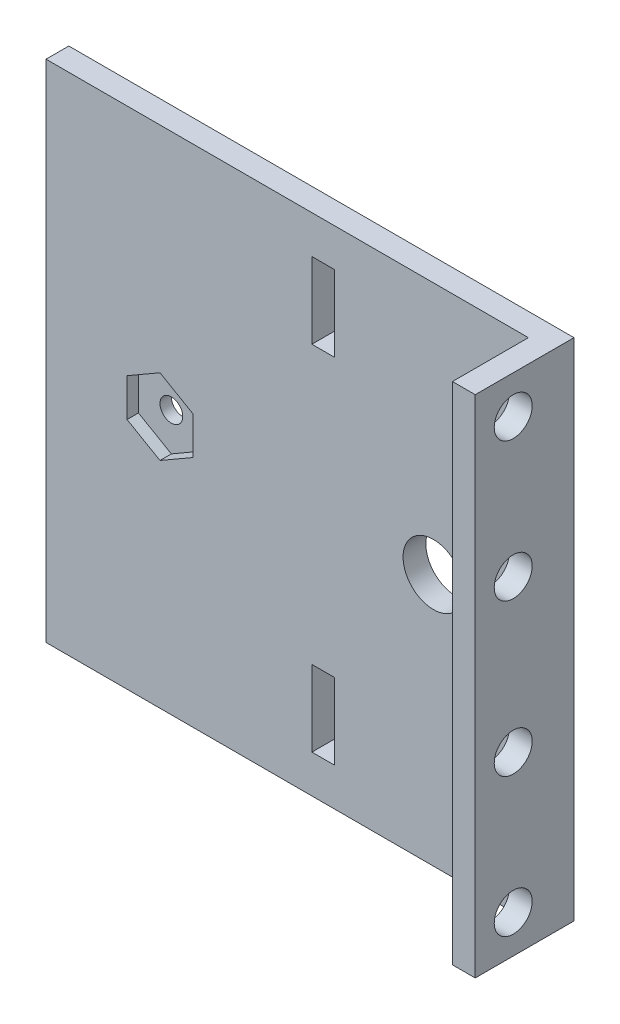
SolidWorks part; units mm, degrees
ref_plane "Front Plane" through (0, 0, 0) normal (0, 0, 1) x (1, 0, 0)
ref_plane "Top Plane" through (0, 0, 0) normal (0, 1, 0) x (1, 0, 0)
ref_plane "Right Plane" through (0, 0, 0) normal (1, 0, 0) x (0, 0, -1)
sketch "Sketch1" plane through (0, 0, 0) normal (0, 0, 1) x (1, 0, 0)
  line L1 (-33.25, 33.25) -> (33.25, 33.25)
  line L2 (-33.25, 33.25) -> (-33.25, -33.25)
  line L3 (-33.25, -33.25) -> (33.25, -33.25)
  line L4 (33.25, 33.25) -> (33.25, -33.25)
  line L5 (-33.25, 33.25) -> (33.25, -33.25) construction
  line L6 (-33.25, -33.25) -> (33.25, 33.25) construction
  circle A0 centre (17.75, 0) radius 4
  point P0 (0, 0)
  dimension "D4" = 8
  dimension "D1" = 66.5
  dimension "D2" = 66.5
  dimension "D3" = 15.5
  dimension "D5" = 33.25
extrude "Boss-Extrude1" add sketch "Sketch1" along normal blind 3
sketch "Sketch3" plane through (0, 0, 3) normal (0, 0, 1) x (1, 0, 0)
  line L0 (33.25, 33.25) -> (-33.25, 33.25) construction
  line L1 (33.25, -33.25) -> (30.25, -33.25)
  line L2 (33.25, -33.25) -> (33.25, 33.25)
  line L3 (33.25, 33.25) -> (30.25, 33.25)
  line L4 (30.25, -33.25) -> (30.25, 33.25)
  dimension "D1" = 3
extrude "Boss-Extrude2" add sketch "Sketch3" along normal blind 10
sketch "Sketch5" plane through (33.25, 0, 0) normal (1, 0, 0) x (0, 0, -1)
  line L0 (-13, -33.25) -> (0, -33.25) construction
  line L1 (-13, -33.25) -> (-13, 33.25) construction
  circle A0 centre (-8, -28.25) radius 2.5
  circle A1 centre (-8, -10) radius 2.5
  point P8 (-6.5, -33.25)
  dimension "D1" = 5
  dimension "D4" = 5
  dimension "D2" = 5
  dimension "D3" = 5
  dimension "D5" = 23.25
  dimension "D6" = 5
extrude "Cut-Extrude1" cut sketch "Sketch5" against normal up to next
mirror "Mirror2" about plane through (0, 0, 0) normal (0, 1, 0) of "Cut-Extrude1"
sketch "Sketch6" plane through (0, 0, 0) normal (0, 0, -1) x (-1, 0, 0)
  line L0 (-33.25, -33.25) -> (-33.25, 33.25) construction
  line L1 (-1.75, 28.25) -> (-4.75, 28.25)
  line L2 (-1.75, 28.25) -> (-1.75, 18.25)
  line L3 (-1.75, 18.25) -> (-4.75, 18.25)
  line L4 (-4.75, 28.25) -> (-4.75, 18.25)
  line L5 (-33.25, 33.25) -> (33.25, 33.25) construction
  dimension "D1" = 31.5
  dimension "D2" = 10
  dimension "D3" = 3
  dimension "D4" = 5
extrude "Cut-Extrude2" cut sketch "Sketch6" against normal up to next
mirror "Mirror3" about plane through (0, 0, 0) normal (0, 1, 0) of "Cut-Extrude2"
sketch "Sketch7" plane through (0, 0, 3) normal (0, 0, -1) x (-1, 0, 0)
  line L0 (7.15, 0) -> (-7.15, 0) construction
  line L1 (18.25, -5) -> (22.5801, -2.5)
  line L2 (22.5801, -2.5) -> (22.5801, 2.5)
  line L3 (22.5801, 2.5) -> (18.25, 5)
  line L4 (18.25, 5) -> (13.9199, 2.5)
  line L5 (13.9199, 2.5) -> (13.9199, -2.5)
  line L6 (13.9199, -2.5) -> (18.25, -5)
  line L7 (-33.25, -33.25) -> (-33.25, 33.25) construction
  circle A0 centre (18.25, 0) radius 4.3301 construction
  point P14 (18.3891, 0.6711)
  dimension "D1" = 5
  dimension "D2" = 51.5
extrude "Cut-Extrude5" cut sketch "Sketch7" along normal blind 1.5
sketch "Sketch9" plane through (0, 0, 0) normal (0, 0, -1) x (-1, 0, 0)
  line L0 (33.25, -33.25) -> (-33.25, -33.25) construction
  line L1 (-33.25, -33.25) -> (-33.25, 33.25) construction
  circle A0 centre (18.25, 0) radius 1.5
  dimension "D1" = 3
  dimension "D2" = 33.25
  dimension "D3" = 51.5
extrude "Cut-Extrude6" cut sketch "Sketch9" against normal up to next
